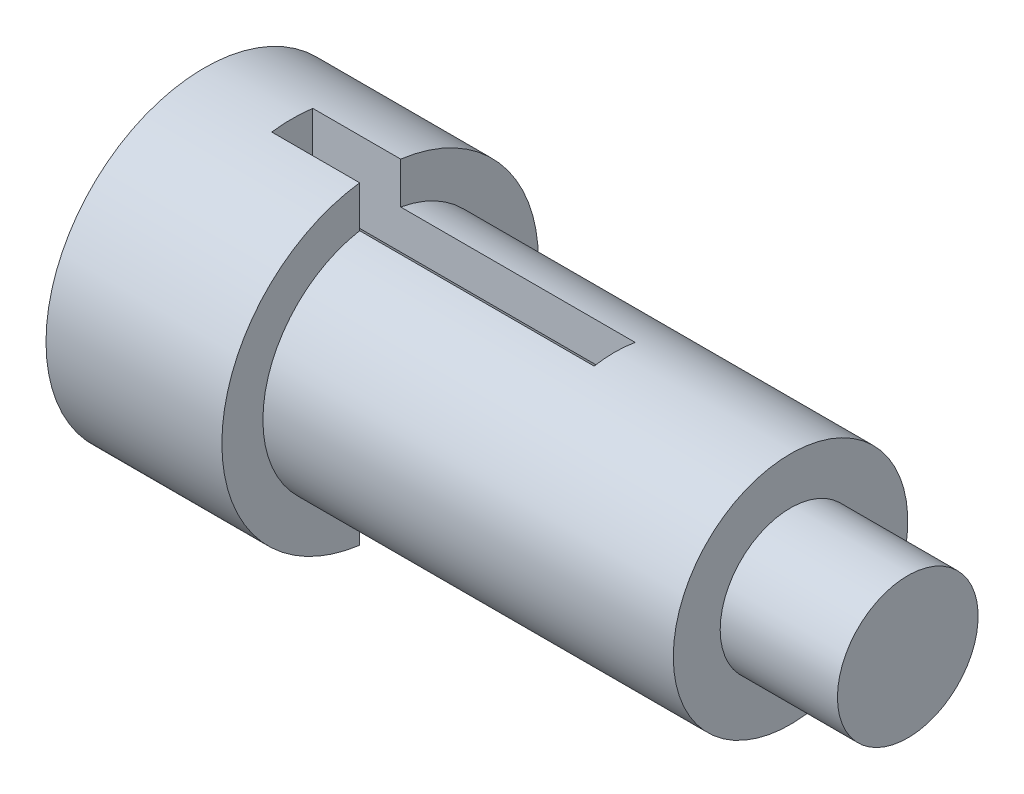
SolidWorks part; units mm, degrees
ref_plane "Front Plane" through (0, 0, 0) normal (0, 0, 1) x (1, 0, 0)
ref_plane "Top Plane" through (0, 0, 0) normal (0, 1, 0) x (1, 0, 0)
ref_plane "Right Plane" through (0, 0, 0) normal (1, 0, 0) x (0, 0, -1)
sketch "Sketch1" plane through (0, 0, 0) normal (0, 1, 0) x (1, 0, 0)
  line L0 (0, 0) -> (120, 0) construction
  line L1 (120, 0) -> (120, 12)
  line L2 (120, 12) -> (100, 12)
  line L3 (100, 12) -> (100, 20)
  line L4 (100, 20) -> (30, 20)
  line L5 (30, 20) -> (30, 27)
  line L6 (30, 27) -> (0, 27)
  line L7 (0, 27) -> (0, 13.5)
  line L8 (0, 13.5) -> (85, 13.5)
  line L9 (85, 13.5) -> (85, 0)
  line L10 (85, 0) -> (120, 0)
  dimension "D1" = 120
  dimension "D2" = 20
  dimension "D3" = 70
  dimension "D4" = 30
  dimension "D5" = 12
  dimension "D6" = 27
  dimension "D7" = 20
  dimension "D8" = 13.5
  dimension "D9" = 85
  dimension "D10" = 13.5
revolve "Revolve1" add sketch "Sketch1" angle 360 about L0
sketch "Sketch2" plane through (0, 0, 0) normal (0, 1, 0) x (1, 0, 0)
  line L0 (0, 0) -> (89.873, 0) construction
  line L1 (0, 27) -> (0, -27) construction
  line L2 (70, -3.5) -> (15, -3.5)
  line L3 (70, -3.5) -> (70, 3.5)
  line L4 (70, 3.5) -> (15, 3.5)
  line L5 (15, -3.5) -> (15, 3.5)
  line L6 (70, -3.5) -> (15, 3.5) construction
  line L7 (70, 3.5) -> (15, -3.5) construction
  point P3 (42.5, 0)
  dimension "D1" = 7
  dimension "D2" = 55
  dimension "D3" = 15
extrude "Cut-Extrude1" cut sketch "Sketch2" against normal through all both and the other way through all
